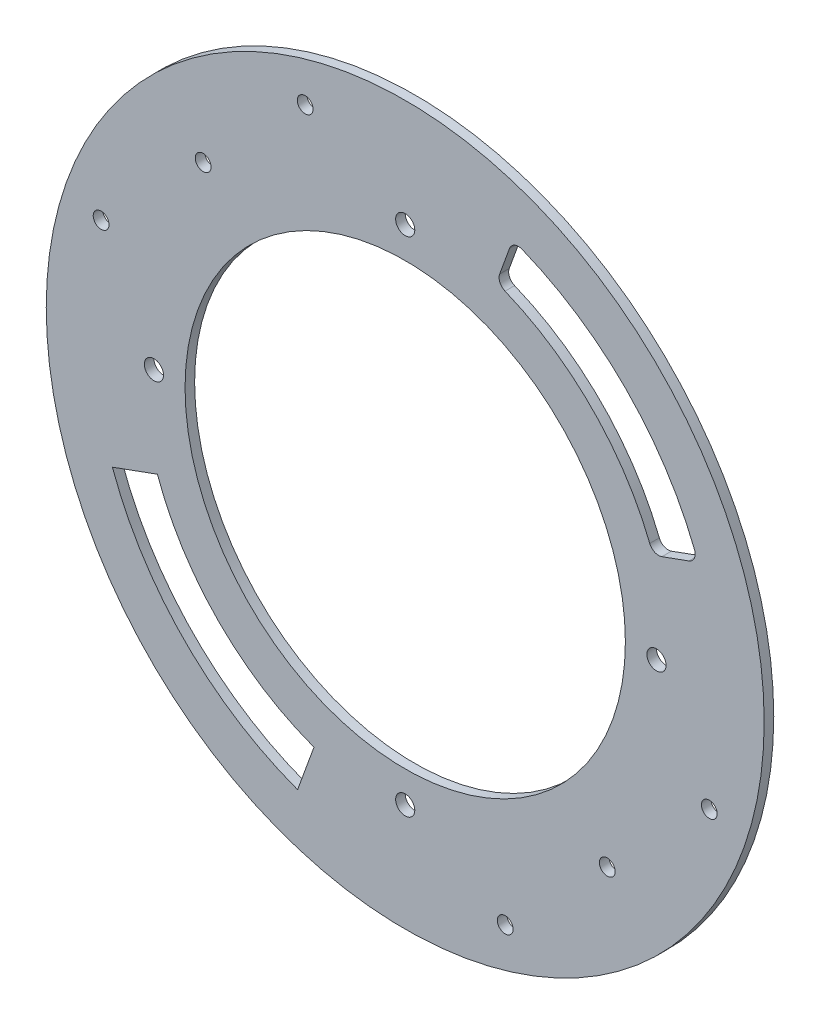
SolidWorks part; units mm, degrees
material "Thornel Mat VMA"
ref_plane "前视基准面" through (0, 0, 0) normal (0, 0, 1) x (1, 0, 0)
ref_plane "上视基准面" through (0, 0, 0) normal (0, 1, 0) x (1, 0, 0)
ref_plane "右视基准面" through (0, 0, 0) normal (1, 0, 0) x (0, 0, -1)
sketch "草图1" plane through (0, 0, 0) normal (0, 0, 1) x (1, 0, 0)
  circle A0 centre (-52.5, 0) radius 2
  circle A1 centre (0, 52.5) radius 2
  circle A2 centre (52.5, 0) radius 2
  circle A3 centre (0, -52.5) radius 2
  circle A4 centre (0, 0) radius 46
  circle A5 centre (0, 0) radius 75
  circle A6 centre (0, 0) radius 50 construction
  point P12 (0, 0)
  dimension "D1" = 2
  dimension "D2" = 52.5
  dimension "D4" = 46
  dimension "D5" = 75
  dimension "D6" = 50
  dimension "D3" = 4
extrude "凸台-拉伸1" add sketch "草图1" along normal blind 2
sketch "草图2" plane through (0, 0, 2) normal (0, 0, 1) x (1, 0, 0)
  circle A0 centre (0, 69) radius 1.5
  circle A1 centre (69, 0) radius 1.5
  circle A2 centre (0, -69) radius 1.5
  circle A3 centre (-69, 0) radius 1.5
  point P12 (0, 0)
  dimension "D1" = 1.5
  dimension "D2" = 69
  dimension "D3" = 4
sketch "草图3" plane through (0, 0, 2) normal (0, 0, 1) x (1, 0, 0)
  line L2 (0, 0) -> (0, 55) construction
  line L3 (0, 0) -> (-65, 0) construction
  line L4 (-51.776, -18.5539) -> (-61.173, -21.9742)
  line L5 (-19.0642, -51.5903) -> (-22.4844, -60.9873)
  line L8 (51.776, 18.5539) -> (61.173, 21.9742)
  line L9 (19.0642, 51.5903) -> (22.4844, 60.9873)
  arc A2 (-61.173, -21.9742) -> (-22.4844, -60.9873) centre (0, 0) ccw
  arc A3 (-51.776, -18.5539) -> (-19.0642, -51.5903) centre (0, 0) ccw
  arc A6 (61.173, 21.9742) -> (22.4844, 60.9873) centre (0, 0) ccw
  arc A7 (51.776, 18.5539) -> (19.0642, 51.5903) centre (0, 0) ccw
  point P23 (0, 0)
extrude "切除-拉伸2" cut sketch "草图3" against normal blind 10
sketch "草图5" plane through (0, 0, 2) normal (0, 0, 1) x (1, 0, 0)
  line L0 (0, 0) -> (39.0824, 38.6984) construction
  line L1 (42.2165, -42.6353) -> (81.2988, -3.9369) construction
  line L2 (-42.2165, 42.6353) -> (-3.1341, 81.3337) construction
  line L3 (-42.2165, 42.6353) -> (42.2165, -42.6353) construction
  line L4 (42.2165, -42.6353) -> (81.2988, -3.9369) construction
  arc A0 (51.776, 18.5539) -> (19.0642, 51.5903) centre (0, 0) ccw construction
  circle A1 centre (-63.5341, 21.5271) radius 1.65
  circle A2 centre (-42.2165, 42.6353) radius 1.65
  circle A3 centre (-20.8988, 63.7435) radius 1.65
  circle A4 centre (63.5341, -21.5271) radius 1.65
  circle A5 centre (42.2165, -42.6353) radius 1.65
  circle A6 centre (20.8988, -63.7435) radius 1.65
  dimension "D3" = 3.3
  dimension "D4" = 3.3
  dimension "D5" = 3.3
  dimension "D7" = 30
  dimension "D6" = 30
  dimension "D2" = 60
extrude "切除-拉伸3" cut sketch "草图5" against normal blind 10
sketch "草图6" plane through (0, 0, 2) normal (0, 0, 1) x (1, 0, 0)
  line L0 (-61.173, -21.9742) -> (-70.5842, -25.3548)
  line L1 (-22.4844, -60.9873) -> (-25.9435, -70.37)
  circle A0 centre (0, 0) radius 75 construction
  arc A1 (-61.173, -21.9742) -> (-22.4844, -60.9873) centre (0, 0) ccw construction
  arc A2 (-70.5842, -25.3548) -> (-25.9435, -70.37) centre (0, 0) ccw
  arc A3 (-61.173, -21.9742) -> (-22.4844, -60.9873) centre (0, 0) ccw
fillet "圆角2" radius 2 4 edges at (51.776, 18.5539, 1) (19.0642, 51.5903, 1) (61.173, 21.9742, 1) (22.4844, 60.9873, 1)
